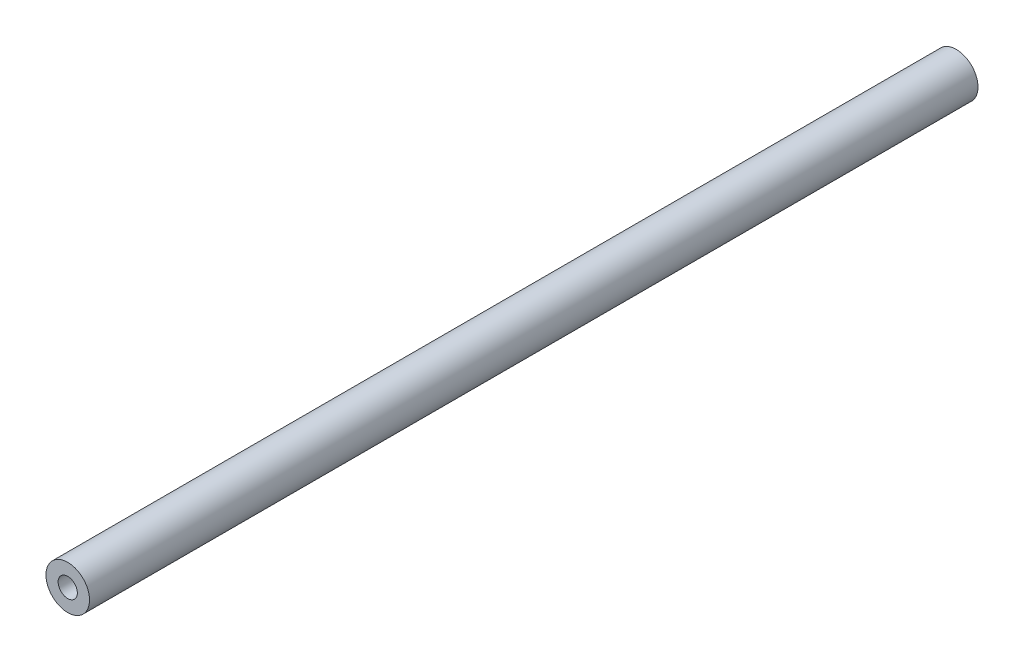
SolidWorks part; units mm, degrees
ref_plane "Front Plane" through (0, 0, 0) normal (0, 0, 1) x (1, 0, 0)
ref_plane "Top Plane" through (0, 0, 0) normal (0, 1, 0) x (1, 0, 0)
ref_plane "Right Plane" through (0, 0, 0) normal (1, 0, 0) x (0, 0, -1)
sketch "Sketch1" plane through (0, 0, 0) normal (0, 0, 1) x (1, 0, 0)
  circle A0 centre (0, 0) radius 3.9688
  dimension "D1" = 7.9375
extrude "Boss-Extrude1" add sketch "Sketch1" along normal mid plane 161.925
hole_wizard "#6-32 Tapped Hole1" positions "Sketch3" profile "Sketch2" tap size "#6-32" standard "ANSI Inch"
sketch "Sketch3" plane through (0, 0, -80.9625) normal (0, 0, -1) x (-1, 0, 0)
  point P0 (0, 0)
sketch "Sketch2" plane through (0, 0, -80.9625) normal (1, 0, 0) x (0, 1, 0)
  line L0 (0, 0) -> (0, 10.2107)
  line L1 (0, 10.2107) -> (1.3525, 9.398)
  line L2 (1.3525, 9.398) -> (1.3525, 7.112)
  line L3 (1.3525, 7.112) -> (1.7526, 7.112)
  line L4 (1.7526, 7.112) -> (1.7526, 0)
  line L5 (1.7526, 0) -> (0, 0)
  line L10 (0, 10.2107) -> (-1.3526, 9.398) construction
  line L11 (0, -6.35) -> (0, 107.95) construction
  dimension "Tap Drill Dia." = 2.7051
  dimension "Tap Drill Depth" = 9.398
  dimension "Thread Major Dia." = 3.5052
  dimension "Thread Depth" = 7.112
  dimension "Drill Angle" = 118
hole_wizard "#6-32 Tapped Hole2" positions "Sketch5" profile "Sketch4" tap size "#6-32" standard "ANSI Inch"
sketch "Sketch5" plane through (0, 0, 80.9625) normal (0, 0, 1) x (1, 0, 0)
  point P0 (0, 0)
sketch "Sketch4" plane through (0, 0, 80.9625) normal (1, 0, 0) x (0, -1, 0)
  line L0 (0, 0) -> (0, 10.2107)
  line L1 (0, 10.2107) -> (1.3525, 9.398)
  line L2 (1.3525, 9.398) -> (1.3525, 7.112)
  line L3 (1.3525, 7.112) -> (1.7526, 7.112)
  line L4 (1.7526, 7.112) -> (1.7526, 0)
  line L5 (1.7526, 0) -> (0, 0)
  line L10 (0, 10.2107) -> (-1.3526, 9.398) construction
  line L11 (0, -6.35) -> (0, 107.95) construction
  dimension "Tap Drill Dia." = 2.7051
  dimension "Tap Drill Depth" = 9.398
  dimension "Thread Major Dia." = 3.5052
  dimension "Thread Depth" = 7.112
  dimension "Drill Angle" = 118
